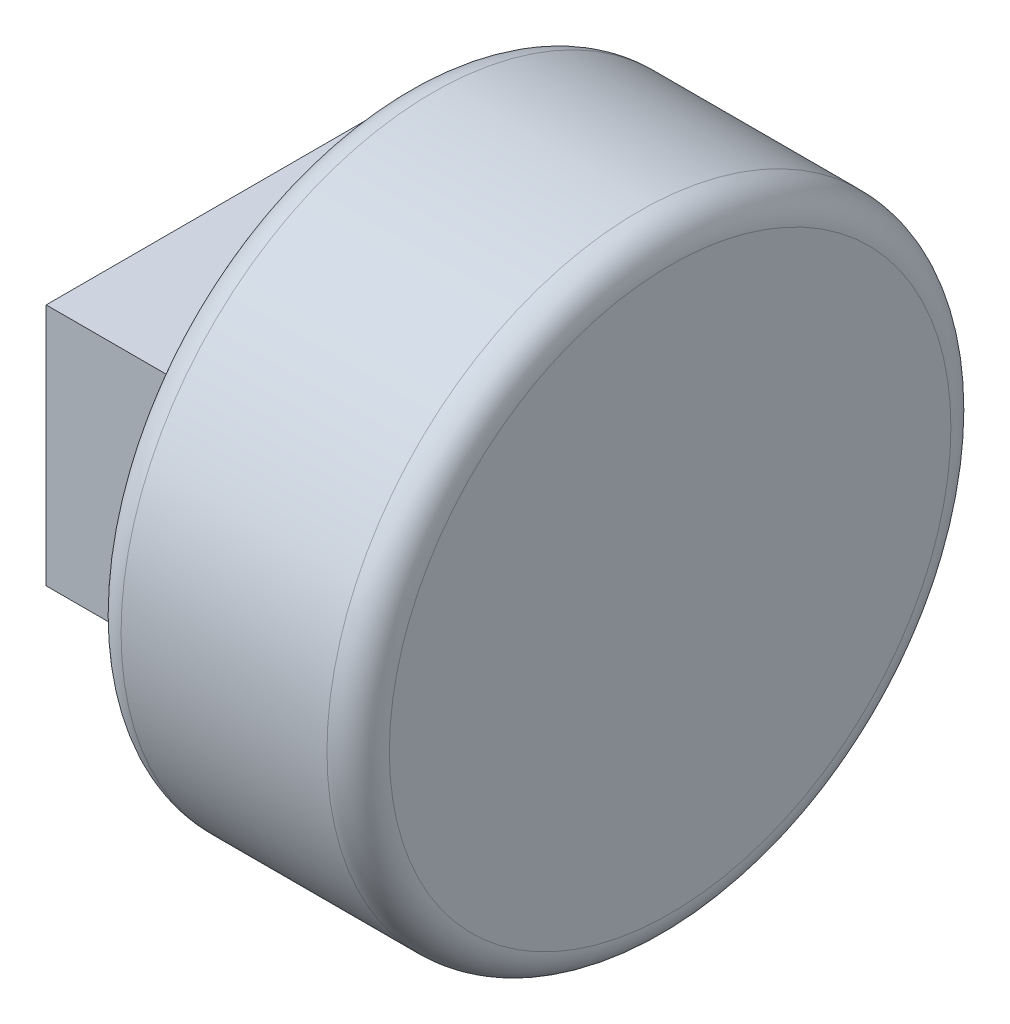
SolidWorks part; units mm, degrees
ref_plane "前视基准面" through (0, 0, 0) normal (0, 0, 1) x (1, 0, 0)
ref_plane "上视基准面" through (0, 0, 0) normal (0, 1, 0) x (1, 0, 0)
ref_plane "右视基准面" through (0, 0, 0) normal (1, 0, 0) x (0, 0, -1)
sketch "草图2" plane through (0, 0, 0) normal (1, 0, 0) x (0, 0, -1)
  line L1 (-30, 19.5) -> (30, 19.5)
  line L2 (-30, 19.5) -> (-30, -19.5)
  line L3 (-30, -19.5) -> (30, -19.5)
  line L4 (30, 19.5) -> (30, -19.5)
  line L5 (-30, 19.5) -> (30, -19.5) construction
  line L6 (-30, -19.5) -> (30, 19.5) construction
  point P0 (0, 0)
  dimension "D1" = 60
  dimension "D2" = 39
extrude "凸台-拉伸1" add sketch "草图2" along normal blind 70
sketch "草图3" plane through (70, 0, 0) normal (1, 0, 0) x (0, 0, -1)
  circle A0 centre (0, 0) radius 50
extrude "凸台-拉伸2" add sketch "草图3" against normal blind 43
fillet "圆角1" radius 5 1 edges at (70, 0, -50)
fillet "圆角2" radius 5 1 edges at (27, 0, -50)
sketch "草图4" plane through (0, 19.5, 0) normal (0, 1, 0) x (1, 0, 0)
  line L0 (0, 0) -> (13, 0) construction
  line L1 (0, 30) -> (27, 30) construction
  line L2 (0, 30) -> (0, -30) construction
  line L3 (0, -30) -> (27, -30) construction
  line L4 (27, 30) -> (27, -30) construction
  line L5 (13.5, -30) -> (13.5, 30) construction
  line L6 (0, 0) -> (27, 0) construction
  circle A0 centre (13, 0) radius 1.5
  point P320 (13.5, 0)
extrude "切除-拉伸1" cut sketch "草图4" against normal blind 3.5
sketch "草图5" plane through (0, -19.5, 0) normal (0, -1, 0) x (1, 0, 0)
  line L0 (0, 0) -> (8, 0) construction
  line L1 (0, 30) -> (27, 30) construction
  line L2 (0, 30) -> (0, -30) construction
  line L3 (0, -30) -> (27, -30) construction
  line L4 (27, 30) -> (27, -30) construction
  line L5 (13.5, -30) -> (13.5, 30) construction
  line L6 (0, 0) -> (27, 0) construction
  line L7 (8, 0) -> (8, -13.25) construction
  line L8 (8, 0) -> (8, 13.5) construction
  circle A0 centre (8, 13.5) radius 1.5
  circle A1 centre (8, -13.25) radius 1.5
  point P328 (13.5, 0)
extrude "切除-拉伸2" cut sketch "草图5" against normal blind 3.5
